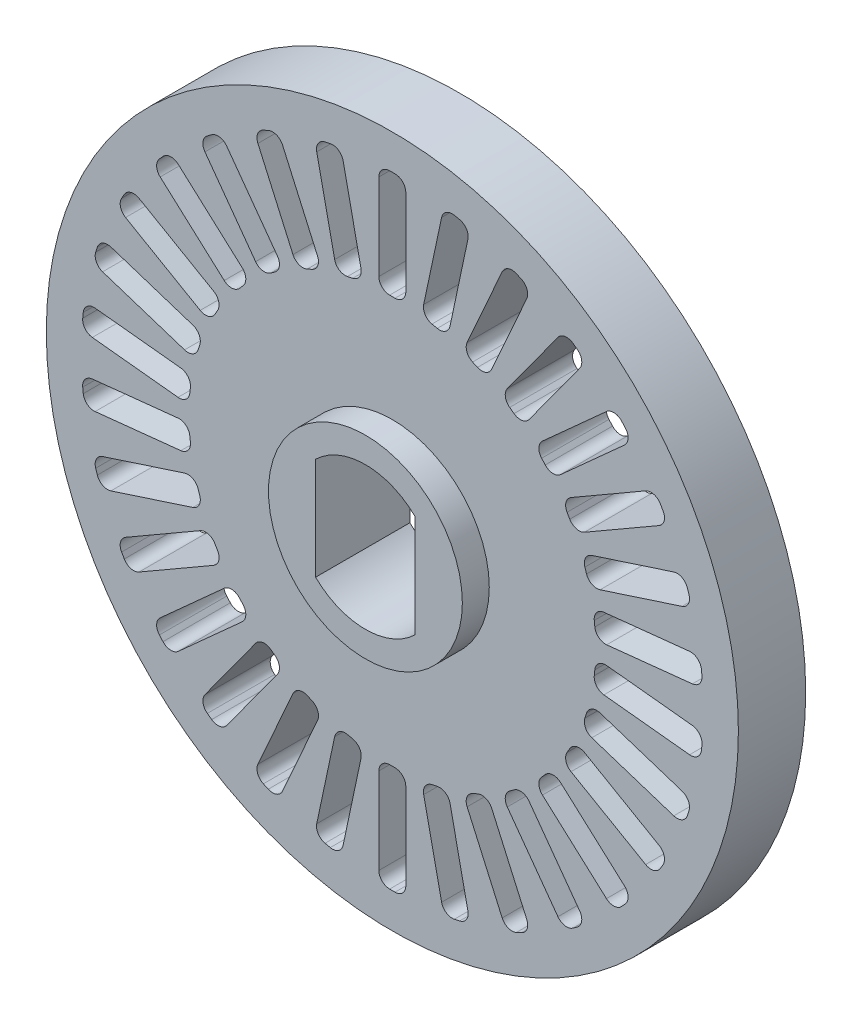
SolidWorks part; units mm, degrees
ref_plane "Ebene vorne" through (0, 0, 0) normal (0, 0, 1) x (1, 0, 0)
ref_plane "Ebene oben" through (0, 0, 0) normal (0, 1, 0) x (1, 0, 0)
ref_plane "Ebene rechts" through (0, 0, 0) normal (1, 0, 0) x (0, 0, -1)
sketch "Skizze1" plane through (0, 0, 0) normal (0, 0, 1) x (1, 0, 0)
  circle A0 centre (0, 0) radius 12.85
  dimension "D1" = 25.7
extrude "Aufsatz-Linear austragen1" add sketch "Skizze1" along normal blind 2.5
sketch "Skizze2" plane through (0, 0, 2.5) normal (0, 0, 1) x (1, 0, 0)
  circle A0 centre (0, 0) radius 3.6
  dimension "D1" = 7.2
extrude "Aufsatz-Linear austragen2" add sketch "Skizze2" along normal blind 1
sketch "Skizze4" plane through (0, 0, 3.5) normal (0, 0, 1) x (1, 0, 0)
  line L0 (0, 0) -> (0, 3.6) construction
  line L1 (-1.85, 1.8974) -> (-1.85, -1.8974)
  line L2 (1.85, 1.8974) -> (1.85, -1.8974)
  arc A0 (-1.85, -1.8974) -> (1.85, -1.8974) centre (0, 0) ccw
  circle A1 centre (0, 0) radius 3.6 construction
  arc A2 (1.85, 1.8974) -> (-1.85, 1.8974) centre (0, 0) ccw
  dimension "D1" = 5.3
  dimension "D2" = 3.7
extrude "Schnitt-Linear austragen2" cut sketch "Skizze4" against normal through all
sketch "Skizze3" plane through (0, 0, 2.5) normal (0, 0, 1) x (1, 0, 0)
  line L0 (0, 0) -> (0, 13.5282) construction
  line L2 (-0.1, 11.55) -> (0.1, 11.55)
  line L3 (-0.5, 11.15) -> (-0.5, 7.95)
  line L4 (-0.1, 7.55) -> (0.1, 7.55)
  line L5 (0.5, 11.15) -> (0.5, 7.95)
  line L6 (-0.5, 11.55) -> (0.5, 7.55) construction
  line L7 (-0.5, 7.55) -> (0.5, 11.55) construction
  circle A2 centre (0, 0) radius 12.85 construction
  arc A3 (-0.5, 7.95) -> (-0.1, 7.55) centre (-0.1, 7.95) ccw
  arc A4 (0.1, 7.55) -> (0.5, 7.95) centre (0.1, 7.95) ccw
  arc A5 (0.1, 11.55) -> (0.5, 11.15) centre (0.1, 11.15) cw
  arc A6 (-0.1, 11.55) -> (-0.5, 11.15) centre (-0.1, 11.15) ccw
  point P3 (0, 9.55)
  dimension "D4" = 0.4
  dimension "D1" = 4
  dimension "D2" = 1
  dimension "D3" = 11.55
extrude "Schnitt-Linear austragen1" cut sketch "Skizze3" against normal up to next
pattern_circular "Kreismuster1" count 30 over 360 about axis through (0, 0, 0) along (0, 0, 1) of "Schnitt-Linear austragen1"
